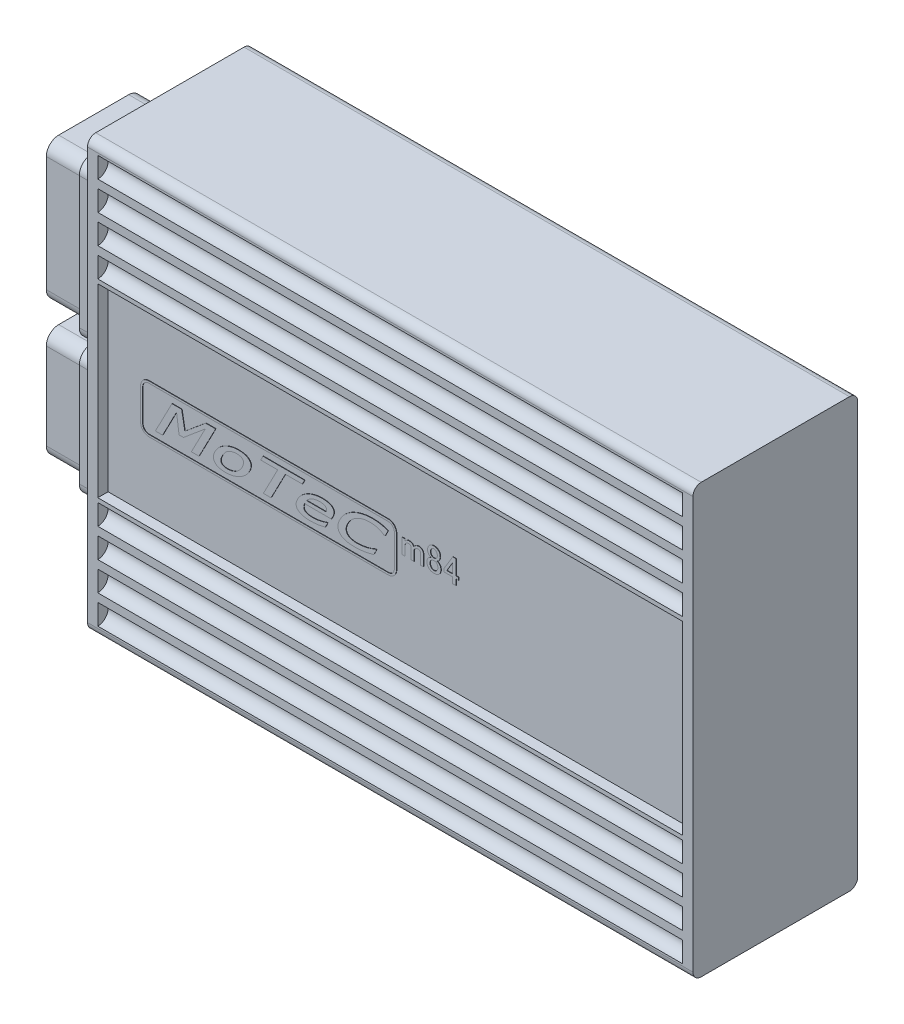
SolidWorks part; units mm, degrees
material "ｽﾁﾚﾝ ﾌﾞﾀｼﾞｴﾝｺﾞﾑ(SBR)"
ref_plane "正面" through (0, 0, 0) normal (0, 0, 1) x (1, 0, 0)
ref_plane "平面" through (0, 0, 0) normal (0, 1, 0) x (1, 0, 0)
ref_plane "右側面" through (0, 0, 0) normal (1, 0, 0) x (0, 0, -1)
sketch "ｽｹｯﾁ1" plane through (0, 0, 0) normal (0, 0, 1) x (1, 0, 0)
  line L1 (-73.5, -52) -> (73.5, -52)
  line L2 (-73.5, -52) -> (-73.5, 52)
  line L3 (-73.5, 52) -> (73.5, 52)
  line L4 (73.5, -52) -> (73.5, 52)
  line L5 (-73.5, -52) -> (73.5, 52) construction
  line L6 (-73.5, 52) -> (73.5, -52) construction
  point P0 (0, 0)
extrude "ﾎﾞｽ - 押し出し1" add sketch "ｽｹｯﾁ1" along normal blind 40
fillet "ﾌｨﾚｯﾄ1" radius 2 4 edges at (0, -52, 0) (0, -52, 40) (0, 52, 0) (0, 52, 40)
sketch "ｽｹｯﾁ5" plane through (0, 0, 0) normal (0, 0, -1) x (-1, 0, 0)
  line L0 (73.5, 50) -> (73.5, -50) construction
  line L1 (-73.5, 22.5) -> (73.5, 22.5)
  line L2 (-73.5, 22.5) -> (-73.5, -22.5)
  line L3 (-73.5, -22.5) -> (73.5, -22.5)
  line L4 (73.5, 22.5) -> (73.5, -22.5)
  line L5 (-73.5, 22.5) -> (73.5, -22.5) construction
  line L6 (-73.5, -22.5) -> (73.5, 22.5) construction
  point P0 (0, 0)
extrude "ｶｯﾄ - 押し出し1" cut sketch "ｽｹｯﾁ5" against normal blind 2.5
sketch "ｽｹｯﾁ6" plane through (-73.5, 0, 0) normal (-1, 0, 0) x (0, 0, 1)
  line L0 (0, 49.5) -> (0, 44.5)
  line L1 (0, 42.5) -> (0, 37.5)
  line L2 (0, 35.5) -> (0, 30.5)
  line L3 (0, 50) -> (0, 22.5) construction
  line L4 (0, 28.5) -> (0, 23.5)
  line L7 (40, 28.5) -> (40, 23.5)
  line L8 (40, 35.5) -> (40, 30.5)
  line L9 (40, 42.5) -> (40, 37.5)
  line L10 (40, 49.5) -> (40, 44.5)
  arc A0 (0, 44.5) -> (0, 49.5) centre (0, 47) ccw
  arc A1 (0, 37.5) -> (0, 42.5) centre (0, 40) ccw
  arc A2 (0, 30.5) -> (0, 35.5) centre (0, 33) ccw
  arc A3 (0, 23.5) -> (0, 28.5) centre (0, 26) ccw
  arc A4 (40, 23.5) -> (40, 28.5) centre (40, 26) cw
  arc A5 (40, 30.5) -> (40, 35.5) centre (40, 33) cw
  arc A6 (40, 37.5) -> (40, 42.5) centre (40, 40) cw
  arc A7 (40, 44.5) -> (40, 49.5) centre (40, 47) cw
extrude "ｶｯﾄ - 押し出し2" cut sketch "ｽｹｯﾁ6" against normal through all
mirror "ﾐﾗｰ1" about plane through (0, 0, 0) normal (0, 1, 0) of "ｶｯﾄ - 押し出し2"
sketch "ｽｹｯﾁ7" plane through (0, 0, 40) normal (0, 0, 1) x (1, 0, 0)
  line L0 (73.5, -23.5) -> (73.5, 23.5) construction
  line L1 (-73.5, -22.5) -> (73.5, -22.5)
  line L2 (-73.5, -22.5) -> (-73.5, 22.5)
  line L3 (-73.5, 22.5) -> (73.5, 22.5)
  line L4 (73.5, -22.5) -> (73.5, 22.5)
  line L5 (-73.5, -22.5) -> (73.5, 22.5) construction
  line L6 (-73.5, 22.5) -> (73.5, -22.5) construction
  point P0 (0, 0)
extrude "ｶｯﾄ - 押し出し3" cut sketch "ｽｹｯﾁ7" against normal blind 2.5
sketch "ｽｹｯﾁ8" plane through (-73.5, 0, 0) normal (-1, 0, 0) x (0, 0, 1)
  line L0 (2, -52) -> (38, -52)
  line L2 (40, -50) -> (40, 50)
  line L3 (38, 52) -> (2, 52)
  line L4 (0, 50) -> (0, -50)
  arc A0 (38, -52) -> (40, -50) centre (38, -50) ccw
  arc A1 (0, -50) -> (2, -52) centre (2, -50) ccw
  arc A2 (2, 52) -> (0, 50) centre (2, 50) ccw
  arc A3 (40, 50) -> (38, 52) centre (38, 50) ccw
  dimension "D1" = 2
extrude "ﾎﾞｽ - 押し出し4" add sketch "ｽｹｯﾁ8" against normal blind 2.5
sketch "ｽｹｯﾁ9" plane through (73.5, 0, 0) normal (1, 0, 0) x (0, 0, -1)
  line L0 (-38, -52) -> (-2, -52)
  line L2 (0, -50) -> (0, 50)
  line L3 (-2, 52) -> (-38, 52)
  line L4 (-40, 50) -> (-40, -50)
  arc A1 (-38, 52) -> (-40, 50) centre (-38, 50) ccw
  arc A2 (0, 50) -> (-2, 52) centre (-2, 50) ccw
  arc A3 (-2, -52) -> (0, -50) centre (-2, -50) ccw
  arc A4 (-40, -50) -> (-38, -52) centre (-38, -50) ccw
  dimension "D1" = 2
extrude "ﾎﾞｽ - 押し出し5" add sketch "ｽｹｯﾁ9" against normal blind 2.5
sketch "ｽｹｯﾁ10" plane through (0, 0, 37.5) normal (0, 0, 1) x (1, 0, 0)
  line L0 (-61, 5.38) -> (-2.9, 5.38)
  line L1 (-61, 5.88) -> (-2.9, 5.88)
  line L2 (-48.818, -3.88) -> (-50.6846, -3.88)
  line L3 (-61, -5.38) -> (-2.9, -5.38)
  line L4 (-50.6846, -3.88) -> (-47.2953, 2.6347)
  line L5 (-62.5, -3.88) -> (-62.5, 3.88)
  line L6 (-63, -3.88) -> (-63, 3.88)
  line L7 (-1.4, 3.88) -> (-1.4, -3.88)
  line L8 (-2.9, -5.88) -> (-61, -5.88)
  line L9 (-0.9, 3.88) -> (-0.9, -3.88)
  line L10 (-47.2953, 2.6347) -> (-52.5742, -1.8169)
  line L11 (-52.5742, -1.8169) -> (-53.6672, -1.8169)
  line L12 (-53.6672, -1.8169) -> (-54.2704, 2.6347)
  line L13 (-54.2704, 2.6347) -> (-57.6598, -3.88)
  line L14 (-57.6598, -3.88) -> (-59.4281, -3.88)
  line L15 (-59.4281, -3.88) -> (-55.3895, 3.8811)
  line L16 (-55.3895, 3.8811) -> (-53.0363, 3.8811)
  line L17 (-53.0363, 3.8811) -> (-52.2641, -0.3464)
  line L18 (-52.2641, -0.3464) -> (-47.1924, 3.8811)
  line L19 (-47.1924, 3.8811) -> (-44.7793, 3.8811)
  line L20 (-44.7793, 3.8811) -> (-48.818, -3.88)
  line L21 (-23.7279, 2.8005) -> (-27.8541, 2.8005)
  line L22 (-27.8541, 2.8005) -> (-31.3309, -3.88)
  line L23 (-31.3309, -3.88) -> (-33.1975, -3.88)
  line L24 (-33.1975, -3.88) -> (-29.7207, 2.8005)
  line L25 (-29.7207, 2.8005) -> (-33.8469, 2.8005)
  line L26 (-33.8469, 2.8005) -> (-33.285, 3.8811)
  line L27 (-33.285, 3.8811) -> (-23.1661, 3.8811)
  line L28 (-23.1661, 3.8811) -> (-23.7279, 2.8005)
  line L29 (-16.6837, -1.031) -> (-23.1677, -1.031)
  line L30 (-17.8457, -2.3081) -> (-17.5448, -2.3081)
  line L31 (-17.5448, -2.3081) -> (-18.1512, -3.4717)
  line L32 (-16.3675, -0.4231) -> (-16.6837, -1.031)
  line L33 (-22.7071, -0.1468) -> (-17.9915, -0.1468)
  line L34 (-2.9053, 3.3592) -> (-3.6052, 2.0145)
  line L35 (-3.6052, 2.0145) -> (-3.9475, 2.0145)
  line L36 (-6.0306, -2.0134) -> (-5.7005, -2.0134)
  line L37 (-5.7005, -2.0134) -> (-6.3944, -3.3458)
  arc A0 (-62.5, -3.88) -> (-61, -5.38) centre (-61, -3.88) ccw
  arc A1 (-63, -3.88) -> (-61, -5.88) centre (-61, -3.88) ccw
  arc A2 (-2.9, -5.38) -> (-1.4, -3.88) centre (-2.9, -3.88) ccw
  arc A3 (-2.9, -5.88) -> (-0.9, -3.88) centre (-2.9, -3.88) ccw
  arc A4 (-0.9, 3.88) -> (-2.9, 5.88) centre (-2.9, 3.88) ccw
  arc A5 (-1.4, 3.88) -> (-2.9, 5.38) centre (-2.9, 3.88) ccw
  arc A6 (-61, 5.38) -> (-62.5, 3.88) centre (-61, 3.88) ccw
  arc A7 (-61, 5.88) -> (-63, 3.88) centre (-61, 3.88) ccw
  spline S0 degree 3 poles (-36.5777, -0.9358) (-36.7009, -1.173) (-36.9152, -1.5135) (-37.2513, -1.9317) (-37.5302, -2.2278) (-37.8372, -2.5041) (-38.1693, -2.764) (-38.5283, -3.0057) (-38.9122, -3.2263) (-39.3132, -3.4265) (-39.7277, -3.6013) (-40.1536, -3.7457) (-40.5887, -3.8684) (-41.0349, -3.9619) (-41.649, -4.05) (-42.1174, -4.0762) (-42.4323, -4.0765) knots 0 0 0 0 0.11486 0.17245 0.230506 0.289545 0.349887 0.411704 0.475483 0.540129 0.604325 0.668756 0.733403 0.798605 0.864633 1 1 1 1
  spline S1 degree 3 poles (-42.4323, -4.0765) (-42.5834, -4.0783) (-42.8056, -4.0683) (-43.0953, -4.0494) (-43.2985, -4.0256) (-43.4923, -3.9973) (-43.6765, -3.96) (-43.8518, -3.9174) (-44.0177, -3.8681) (-44.1746, -3.8138) (-44.3211, -3.7497) (-44.4591, -3.6817) (-44.587, -3.6058) (-44.7062, -3.5246) (-44.8151, -3.4352) (-44.9152, -3.3398) (-45.0063, -3.2387) (-45.0858, -3.1309) (-45.1562, -3.0187) (-45.2118, -2.9001) (-45.2596, -2.778) (-45.2917, -2.6499) (-45.3182, -2.5179) (-45.3269, -2.3804) (-45.3297, -2.2389) (-45.3179, -2.0927) (-45.2961, -1.9415) (-45.2643, -1.7849) (-45.2188, -1.6238) (-45.1639, -1.4575) (-45.0707, -1.2253) (-44.9886, -1.0518) (-44.9282, -0.9358) knots 0 0 0 0 0.08649 0.127322 0.166248 0.203584 0.23944 0.273835 0.30684 0.338533 0.36885 0.398333 0.426574 0.453963 0.480825 0.507145 0.533083 0.558634 0.58376 0.608791 0.633551 0.65871 0.684341 0.710499 0.737457 0.765367 0.794373 0.824886 0.856804 0.89016 0.925145 1 1 1 1
  spline S2 degree 3 poles (-44.9282, -0.9358) (-44.8022, -0.6955) (-44.5877, -0.3482) (-44.2489, 0.0764) (-43.9702, 0.375) (-43.6668, 0.6536) (-43.3382, 0.9124) (-42.9843, 1.1516) (-42.6081, 1.372) (-42.2138, 1.5683) (-41.8079, 1.7417) (-41.3903, 1.8851) (-40.9637, 2.0059) (-40.5266, 2.0973) (-39.9262, 2.1872) (-39.4676, 2.2089) (-39.1596, 2.211) knots 0 0 0 0 0.117897 0.176741 0.23572 0.295189 0.355492 0.41727 0.480633 0.544754 0.608501 0.672263 0.736447 0.800971 0.86614 1 1 1 1
  spline S3 degree 3 poles (-39.1596, 2.211) (-39.0055, 2.212) (-38.7785, 2.2044) (-38.4828, 2.1817) (-38.2753, 2.1594) (-38.0778, 2.128) (-37.8898, 2.0917) (-37.7107, 2.0491) (-37.5419, 1.998) (-37.3816, 1.9418) (-37.2315, 1.8774) (-37.0912, 1.8064) (-36.9598, 1.7299) (-36.8387, 1.645) (-36.7263, 1.5549) (-36.624, 1.4574) (-36.5325, 1.3533) (-36.4501, 1.2439) (-36.3803, 1.1288) (-36.3192, 1.0103) (-36.2719, 0.8865) (-36.2349, 0.7587) (-36.2085, 0.6268) (-36.1952, 0.49) (-36.1917, 0.3489) (-36.2017, 0.2032) (-36.2217, 0.0534) (-36.2531, -0.1007) (-36.2938, -0.26) (-36.3488, -0.4229) (-36.4364, -0.6522) (-36.5191, -0.8216) (-36.5777, -0.9358) knots 0 0 0 0 0.087469 0.128832 0.16828 0.205905 0.2423 0.276956 0.310309 0.342367 0.373332 0.402945 0.431585 0.459541 0.4868 0.513298 0.539635 0.565367 0.590919 0.615986 0.640903 0.665995 0.691455 0.717145 0.74387 0.771515 0.799937 0.829554 0.860759 0.893179 0.927103 1 1 1 1
  spline S4 degree 3 poles (-38.346, -0.9358) (-38.2574, -0.7704) (-38.1489, -0.5248) (-38.0457, -0.2002) (-38.0049, 0.0143) (-37.9926, 0.211) (-38.0094, 0.3913) (-38.0597, 0.5536) (-38.1369, 0.6994) (-38.2448, 0.8249) (-38.3747, 0.9354) (-38.5316, 1.0255) (-38.7113, 1.1012) (-38.9167, 1.1584) (-39.2379, 1.2147) (-39.4932, 1.2305) (-39.6708, 1.2286) knots 0 0 0 0 0.165351 0.236136 0.299935 0.35732 0.409486 0.458578 0.506215 0.55393 0.603552 0.655936 0.712748 0.775154 0.843472 1 1 1 1
  spline S5 degree 3 poles (-39.6708, 1.2286) (-39.8529, 1.2297) (-40.1234, 1.2126) (-40.4773, 1.1597) (-40.7328, 1.103) (-40.9807, 1.0286) (-41.2218, 0.9397) (-41.4561, 0.8354) (-41.6821, 0.7134) (-41.9013, 0.5755) (-42.11, 0.417) (-42.309, 0.2388) (-42.4999, 0.0427) (-42.6788, -0.1755) (-42.9131, -0.4938) (-43.0653, -0.7549) (-43.1599, -0.9358) knots 0 0 0 0 0.125748 0.186879 0.246987 0.306363 0.365517 0.424368 0.483349 0.542766 0.603061 0.664139 0.727124 0.791879 0.858893 1 1 1 1
  spline S6 degree 3 poles (-43.1599, -0.9358) (-43.2444, -1.1024) (-43.3583, -1.3453) (-43.4595, -1.6697) (-43.5022, -1.8833) (-43.5179, -2.0794) (-43.5036, -2.2592) (-43.4591, -2.4214) (-43.3855, -2.5663) (-43.2836, -2.6915) (-43.1582, -2.8004) (-43.0096, -2.8929) (-42.8366, -2.9656) (-42.6417, -3.0243) (-42.335, -3.08) (-42.0911, -3.096) (-41.9211, -3.0941) knots 0 0 0 0 0.168476 0.240795 0.305611 0.364297 0.417506 0.467272 0.514892 0.562763 0.611762 0.663944 0.719687 0.780349 0.846975 1 1 1 1
  spline S7 degree 3 poles (-41.9211, -3.0941) (-41.7331, -3.0918) (-41.4531, -3.0796) (-41.0877, -3.0195) (-40.8225, -2.963) (-40.5649, -2.885) (-40.3148, -2.7913) (-40.0706, -2.6823) (-39.8349, -2.5547) (-39.6073, -2.4111) (-39.3924, -2.2487) (-39.1871, -2.0723) (-38.995, -1.8776) (-38.8135, -1.6672) (-38.5852, -1.3596) (-38.4377, -1.1088) (-38.346, -0.9358) knots 0 0 0 0 0.128096 0.190164 0.251852 0.312564 0.373178 0.433506 0.494435 0.555497 0.616445 0.67768 0.739494 0.802466 0.866689 1 1 1 1
  spline S8 degree 3 poles (-23.1677, -1.031) (-23.239, -1.1708) (-23.3273, -1.3838) (-23.38, -1.6756) (-23.3836, -1.8779) (-23.3558, -2.064) (-23.2898, -2.2835) (-23.1916, -2.4213) (-23.1124, -2.4939) knots 0 0 0 0 0.300432 0.436419 0.564515 0.685087 0.794857 1 1 1 1
  spline S9 degree 3 poles (-23.1124, -2.4939) (-23.0171, -2.5853) (-22.8472, -2.6978) (-22.5932, -2.8134) (-22.3737, -2.881) (-22.1311, -2.9328) (-21.7617, -2.9823) (-21.4713, -2.9964) (-21.2704, -2.9958) knots 0 0 0 0 0.202 0.310705 0.427794 0.554064 0.691352 1 1 1 1
  spline S10 degree 3 poles (-21.2704, -2.9958) (-20.9645, -2.9964) (-20.4966, -2.9651) (-19.8657, -2.8697) (-19.4578, -2.787) (-19.1335, -2.7124) (-18.904, -2.6537) (-18.6896, -2.5968) (-18.4904, -2.5414) (-18.3075, -2.4814) (-18.0917, -2.4113) (-17.9411, -2.3484) (-17.8457, -2.3081) knots 0 0 0 0 0.261145 0.399928 0.544803 0.616587 0.684226 0.7471 0.806182 0.860786 0.911516 1 1 1 1
  spline S11 degree 3 poles (-18.1512, -3.4717) (-18.475, -3.5472) (-18.9516, -3.6513) (-19.5758, -3.7713) (-20.0167, -3.8464) (-20.4491, -3.9062) (-21.0272, -3.9606) (-21.4634, -3.9803) (-21.7554, -3.9782) knots 0 0 0 0 0.273424 0.401082 0.522686 0.641161 0.759937 1 1 1 1
  spline S12 degree 3 poles (-21.7554, -3.9782) (-21.9325, -3.9782) (-22.1927, -3.9728) (-22.5319, -3.952) (-22.7704, -3.9305) (-22.9983, -3.9034) (-23.2158, -3.8692) (-23.4231, -3.8303) (-23.6188, -3.7821) (-23.8044, -3.7301) (-23.9792, -3.6721) (-24.1438, -3.6078) (-24.2976, -3.5371) (-24.4413, -3.4607) (-24.5728, -3.3758) (-24.6951, -3.287) (-24.8059, -3.1914) (-24.9057, -3.0909) (-24.9926, -2.984) (-25.0668, -2.8714) (-25.1282, -2.7529) (-25.1775, -2.6295) (-25.2152, -2.5012) (-25.2374, -2.3672) (-25.2483, -2.228) (-25.2465, -2.0837) (-25.2323, -1.9339) (-25.2059, -1.779) (-25.1677, -1.6188) (-25.1143, -1.4541) (-25.0259, -1.2206) (-24.9444, -1.0463) (-24.8838, -0.9297) knots 0 0 0 0 0.093747 0.137709 0.179862 0.220513 0.259166 0.296403 0.332074 0.365856 0.398404 0.429538 0.459352 0.487951 0.5156 0.542146 0.567881 0.592971 0.617041 0.640704 0.664206 0.687544 0.710946 0.734858 0.759308 0.78477 0.811155 0.838897 0.867868 0.898277 0.930422 1 1 1 1
  spline S13 degree 3 poles (-24.8838, -0.9297) (-24.7596, -0.6889) (-24.54, -0.3451) (-24.1967, 0.0779) (-23.9084, 0.374) (-23.5931, 0.6518) (-23.2507, 0.9114) (-22.879, 1.1507) (-22.4832, 1.3708) (-22.0683, 1.5667) (-21.6416, 1.7397) (-21.2059, 1.8857) (-20.7601, 2.0035) (-20.3058, 2.0979) (-19.6825, 2.1863) (-19.2078, 2.2093) (-18.8895, 2.211) knots 0 0 0 0 0.114335 0.17179 0.229874 0.288677 0.349154 0.411205 0.475256 0.540323 0.604903 0.66963 0.734274 0.799596 0.865529 1 1 1 1
  spline S14 degree 3 poles (-18.8895, 2.211) (-18.6048, 2.2099) (-18.1943, 2.1957) (-17.6759, 2.1191) (-17.3417, 2.0438) (-17.0445, 1.9461) (-16.7843, 1.8273) (-16.5608, 1.6854) (-16.3763, 1.5207) (-16.2307, 1.3359) (-16.1253, 1.1324) (-16.062, 0.9113) (-16.0409, 0.6734) (-16.0638, 0.4205) (-16.1471, 0.0427) (-16.2705, -0.2361) (-16.3675, -0.4231) knots 0 0 0 0 0.180062 0.258847 0.330846 0.396281 0.456168 0.511145 0.562887 0.611718 0.659004 0.706791 0.756144 0.809012 0.866596 1 1 1 1
  spline S15 degree 3 poles (-17.9915, -0.1468) (-17.9461, -0.0555) (-17.8865, 0.0815) (-17.8527, 0.2692) (-17.8447, 0.3975) (-17.8607, 0.5196) (-17.8964, 0.6349) (-17.9525, 0.7434) (-18.0288, 0.8451) (-18.1292, 0.9365) (-18.2534, 1.0168) (-18.4034, 1.0814) (-18.5763, 1.1374) (-18.7753, 1.1766) (-19.0885, 1.2199) (-19.3376, 1.2281) (-19.5112, 1.2286) knots 0 0 0 0 0.116957 0.168662 0.217232 0.263196 0.308491 0.3545 0.402079 0.452957 0.508728 0.570212 0.638975 0.71601 0.801566 1 1 1 1
  spline S16 degree 3 poles (-19.5112, 1.2286) (-19.6901, 1.2296) (-19.9551, 1.2158) (-20.3024, 1.173) (-20.5519, 1.1269) (-20.7942, 1.0681) (-21.0289, 0.9984) (-21.2559, 0.9133) (-21.473, 0.8155) (-21.6796, 0.7097) (-21.8724, 0.5999) (-22.0503, 0.4864) (-22.2113, 0.3673) (-22.3597, 0.2473) (-22.5306, 0.0813) (-22.6436, -0.052) (-22.7071, -0.1468) knots 0 0 0 0 0.148913 0.22062 0.291229 0.360047 0.428112 0.494978 0.561724 0.626315 0.68814 0.746401 0.801873 0.85484 0.905156 1 1 1 1
  spline S17 degree 3 poles (-6.3944, -3.3458) (-6.5902, -3.3974) (-6.8702, -3.4618) (-7.2185, -3.5552) (-7.4427, -3.6129) (-7.6661, -3.6705) (-8.0166, -3.7476) (-8.2963, -3.8041) (-8.4943, -3.8416) knots 0 0 0 0 0.281526 0.399182 0.501308 0.603258 0.719903 1 1 1 1
  spline S18 degree 3 poles (-8.4943, -3.8416) (-8.8676, -3.9077) (-9.3444, -3.9804) (-9.9296, -4.0402) (-10.362, -4.069) (-10.6924, -4.0756) (-10.9166, -4.0765) knots 0 0 0 0 0.466732 0.593333 0.724013 1 1 1 1
  spline S19 degree 3 poles (-10.9166, -4.0765) (-11.1224, -4.0785) (-11.4255, -4.0686) (-11.8221, -4.0444) (-12.1026, -4.0187) (-12.3717, -3.9842) (-12.6302, -3.9457) (-12.8771, -3.8954) (-13.1137, -3.8416) (-13.3375, -3.777) (-13.5489, -3.7043) (-13.7484, -3.6255) (-13.9349, -3.5367) (-14.1073, -3.4372) (-14.3203, -3.2993) (-14.4632, -3.1767) (-14.5515, -3.091) knots 0 0 0 0 0.160141 0.235948 0.30913 0.379362 0.447054 0.512417 0.575391 0.635885 0.693558 0.74931 0.80274 0.854105 0.904135 1 1 1 1
  spline S20 degree 3 poles (-14.5515, -3.091) (-14.6332, -3.0081) (-14.7451, -2.8747) (-14.8665, -2.6775) (-14.9392, -2.5203) (-14.9998, -2.3557) (-15.0445, -2.1824) (-15.0729, -2.0004) (-15.0888, -1.8101) (-15.0872, -1.6112) (-15.0661, -1.4045) (-15.0293, -1.1901) (-14.9748, -0.9675) (-14.9028, -0.7377) (-14.7767, -0.413) (-14.6637, -0.1699) (-14.5792, -0.0071) knots 0 0 0 0 0.105347 0.15689 0.209093 0.261831 0.315407 0.370754 0.428362 0.488101 0.550445 0.616222 0.684847 0.757639 0.834008 1 1 1 1
  spline S21 degree 3 poles (-14.5792, -0.0071) (-14.4951, 0.1549) (-14.3581, 0.3917) (-14.1569, 0.6954) (-13.9973, 0.9172) (-13.8265, 1.1317) (-13.6473, 1.3406) (-13.4578, 1.5424) (-13.1913, 1.8022) (-12.8362, 2.1099) (-12.2254, 2.5699) (-11.7239, 2.8586) (-11.3786, 3.0338) knots 0 0 0 0 0.121978 0.18268 0.243425 0.304524 0.365875 0.427326 0.489476 0.614555 0.741086 1 1 1 1
  spline S22 degree 3 poles (-11.3786, 3.0338) (-11.0336, 3.2049) (-10.496, 3.4343) (-9.7453, 3.668) (-9.1567, 3.8174) (-8.5507, 3.9325) (-7.7204, 4.0477) (-7.0883, 4.0758) (-6.6645, 4.0776) knots 0 0 0 0 0.237239 0.359144 0.483968 0.611049 0.738924 1 1 1 1
  spline S23 degree 3 poles (-6.6645, 4.0776) (-6.3521, 4.0784) (-5.8883, 4.0593) (-5.2793, 3.995) (-4.8316, 3.9292) (-4.3774, 3.8355) (-3.7276, 3.6632) (-3.2372, 3.49) (-2.9053, 3.3592) knots 0 0 0 0 0.243327 0.361127 0.476764 0.595548 0.722064 1 1 1 1
  spline S24 degree 3 poles (-3.9475, 2.0145) (-4.1771, 2.184) (-4.5416, 2.4084) (-5.0614, 2.6382) (-5.4679, 2.7721) (-5.8967, 2.874) (-6.5232, 2.9708) (-7.0117, 2.9991) (-7.3461, 2.9969) knots 0 0 0 0 0.237578 0.354907 0.472536 0.593451 0.721574 1 1 1 1
  spline S25 degree 3 poles (-7.3461, 2.9969) (-7.6219, 2.9979) (-8.0311, 2.9755) (-8.5665, 2.9016) (-8.9542, 2.8232) (-9.3368, 2.7185) (-9.8553, 2.5457) (-10.2318, 2.368) (-10.4822, 2.2417) knots 0 0 0 0 0.253906 0.376619 0.497274 0.617832 0.741623 1 1 1 1
  spline S26 degree 3 poles (-10.4822, 2.2417) (-10.7045, 2.1261) (-11.028, 1.9227) (-11.4317, 1.6025) (-11.7296, 1.3332) (-12.0114, 1.0365) (-12.3621, 0.6006) (-12.5845, 0.2402) (-12.7156, -0.0117) knots 0 0 0 0 0.233293 0.354756 0.479582 0.607001 0.735458 1 1 1 1
  spline S27 degree 3 poles (-12.7156, -0.0117) (-12.7817, -0.1391) (-12.8725, -0.3274) (-12.9672, -0.5803) (-13.0257, -0.7553) (-13.0665, -0.9239) (-13.0951, -1.0849) (-13.1092, -1.2379) (-13.1092, -1.4273) (-13.0816, -1.6452) (-13.0027, -1.9554) (-12.8863, -2.1582) (-12.7862, -2.2682) knots 0 0 0 0 0.179369 0.260704 0.337327 0.409738 0.477214 0.541403 0.601498 0.713544 0.814809 1 1 1 1
  spline S28 degree 3 poles (-12.7862, -2.2682) (-12.6661, -2.3989) (-12.4496, -2.5673) (-12.1148, -2.7325) (-11.8285, -2.8305) (-11.5157, -2.9045) (-11.0545, -2.9772) (-10.6945, -2.996) (-10.4484, -2.9958) knots 0 0 0 0 0.211163 0.323577 0.443788 0.571197 0.706507 1 1 1 1
  spline S29 degree 3 poles (-10.4484, -2.9958) (-10.0792, -2.9962) (-9.5258, -2.9642) (-8.7927, -2.864) (-8.244, -2.7575) (-7.6933, -2.6209) (-6.9482, -2.3886) (-6.3948, -2.1771) (-6.0306, -2.0134) knots 0 0 0 0 0.24289 0.364219 0.486645 0.610525 0.737368 1 1 1 1
sketch "ｽｹｯﾁ11" plane through (0, 0, 37.5) normal (0, 0, 1) x (1, 0, 0)
  line L0 (1.1441, 0.0981) -> (0.448, 0.0981)
  line L1 (0.448, 0.0981) -> (0.448, 3.7593)
  line L2 (0.448, 3.7593) -> (1.1441, 3.7593)
  line L3 (1.1441, 3.7593) -> (1.1441, 3.2036)
  line L4 (5.6553, 2.8113) -> (5.6553, 0.0981)
  line L5 (5.6553, 0.0981) -> (4.9592, 0.0981)
  line L6 (4.9592, 0.0981) -> (4.9592, 2.6806)
  line L7 (3.3997, 2.419) -> (3.3997, 0.0981)
  line L8 (3.3997, 0.0981) -> (2.7036, 0.0981)
  line L9 (2.7036, 0.0981) -> (2.7036, 2.6479)
  line L10 (1.1441, 2.3864) -> (1.1441, 0.0981)
  line L11 (8.9655, 3.0075) -> (8.9655, 2.9421)
  line L12 (7.4618, 2.9421) -> (7.4618, 3.0075)
  line L13 (12.7902, 5.7534) -> (13.5421, 5.7534)
  line L14 (13.5421, 5.7534) -> (13.5421, 2.1575)
  line L15 (13.5421, 2.1575) -> (14.2286, 2.1575)
  line L16 (14.2286, 2.1575) -> (14.2286, 1.5388)
  line L17 (14.2286, 1.5388) -> (13.5421, 1.5388)
  line L18 (13.5421, 1.5388) -> (13.5421, 0.0981)
  line L19 (13.5421, 0.0981) -> (12.7684, 0.0981)
  line L20 (12.7684, 0.0981) -> (12.7684, 1.5388)
  line L21 (12.7684, 1.5388) -> (10.6, 1.5388)
  line L22 (10.6, 1.5388) -> (10.6, 2.1902)
  line L23 (10.6, 2.1902) -> (12.7902, 5.7534)
  line L24 (12.7684, 4.5439) -> (11.3192, 2.1575)
  line L25 (11.3192, 2.1575) -> (12.7684, 2.1575)
  line L26 (12.7684, 2.1575) -> (12.7684, 4.5439)
  spline S0 degree 3 poles (1.1441, 3.2036) (1.2091, 3.3006) (1.3165, 3.4324) (1.4761, 3.5832) (1.5982, 3.6709) (1.7237, 3.7398) (1.8965, 3.8054) (2.0336, 3.8248) (2.1248, 3.8247) knots 0 0 0 0 0.289076 0.420056 0.543346 0.660649 0.774007 1 1 1 1
  spline S1 degree 3 poles (2.1248, 3.8247) (2.2225, 3.8255) (2.3653, 3.8154) (2.5475, 3.7813) (2.6714, 3.7462) (2.7859, 3.7001) (2.9253, 3.6249) (3.0183, 3.5525) (3.0728, 3.4978) knots 0 0 0 0 0.28435 0.416051 0.539631 0.658871 0.775162 1 1 1 1
  spline S2 degree 3 poles (3.0728, 3.4978) (3.1259, 3.4441) (3.225, 3.3321) (3.3007, 3.2031) (3.3344, 3.1382) knots 0 0 0 0 0.508066 1 1 1 1
  spline S3 degree 3 poles (3.3344, 3.1382) (3.4009, 3.2461) (3.5142, 3.3952) (3.6946, 3.5595) (3.8391, 3.6553) (3.9921, 3.7317) (4.2138, 3.8066) (4.3918, 3.8235) (4.5112, 3.8247) knots 0 0 0 0 0.266156 0.390354 0.510676 0.628903 0.748675 1 1 1 1
  spline S4 degree 3 poles (4.5112, 3.8247) (4.5937, 3.8239) (4.715, 3.8171) (4.8701, 3.7856) (4.9763, 3.7531) (5.0759, 3.7116) (5.1981, 3.6443) (5.2797, 3.579) (5.3284, 3.5305) knots 0 0 0 0 0.277854 0.406706 0.531659 0.650908 0.768781 1 1 1 1
  spline S5 degree 3 poles (5.3284, 3.5305) (5.3803, 3.4787) (5.4513, 3.3967) (5.5288, 3.2784) (5.576, 3.1891) (5.6103, 3.0972) (5.6454, 2.9726) (5.6558, 2.876) (5.6553, 2.8113) knots 0 0 0 0 0.271081 0.399345 0.522112 0.643458 0.761079 1 1 1 1
  spline S6 degree 3 poles (4.9592, 2.6806) (4.9575, 2.7409) (4.949, 2.8568) (4.9009, 2.9629) (4.8708, 3.0075) knots 0 0 0 0 0.529898 1 1 1 1
  spline S7 degree 3 poles (4.8708, 3.0075) (4.81, 3.0685) (4.6691, 3.1722) (4.4969, 3.2038) (4.4131, 3.2036) knots 0 0 0 0 0.507506 1 1 1 1
  spline S8 degree 3 poles (4.4131, 3.2036) (4.3398, 3.2028) (4.2315, 3.1955) (4.0927, 3.1647) (3.9963, 3.131) (3.9039, 3.0907) (3.7882, 3.0211) (3.7089, 2.9578) (3.6613, 2.9094) knots 0 0 0 0 0.265315 0.391024 0.512886 0.634416 0.754828 1 1 1 1
  spline S9 degree 3 poles (3.6613, 2.9094) (3.5876, 2.833) (3.4593, 2.6878) (3.4011, 2.5024) (3.3997, 2.419) knots 0 0 0 0 0.564258 1 1 1 1
  spline S10 degree 3 poles (2.7036, 2.6479) (2.7041, 2.7153) (2.672, 2.8568) (2.5978, 2.9811) (2.5498, 3.0402) knots 0 0 0 0 0.468245 1 1 1 1
  spline S11 degree 3 poles (2.5498, 3.0402) (2.4931, 3.098) (2.3343, 3.1836) (2.1559, 3.2052) (2.0595, 3.2036) knots 0 0 0 0 0.45309 1 1 1 1
  spline S12 degree 3 poles (2.0595, 3.2036) (1.9447, 3.2054) (1.7132, 3.1598) (1.5193, 3.0255) (1.4384, 2.9421) knots 0 0 0 0 0.496526 1 1 1 1
  spline S13 degree 3 poles (1.4384, 2.9421) (1.3545, 2.8562) (1.2127, 2.6903) (1.1432, 2.4818) (1.1441, 2.3864) knots 0 0 0 0 0.561835 1 1 1 1
  spline S14 degree 3 poles (6.6772, 4.1843) (6.6768, 4.2995) (6.6912, 4.4688) (6.7381, 4.6867) (6.7896, 4.838) (6.8539, 4.9823) (6.9595, 5.1641) (7.0598, 5.287) (7.1349, 5.3611) knots 0 0 0 0 0.266281 0.391515 0.514598 0.635338 0.756207 1 1 1 1
  spline S15 degree 3 poles (7.1349, 5.3611) (7.2002, 5.4253) (7.3073, 5.5139) (7.4705, 5.6021) (7.6011, 5.6584) (7.7419, 5.7001) (7.9453, 5.7439) (8.1052, 5.7528) (8.2136, 5.7534) knots 0 0 0 0 0.233399 0.350616 0.471182 0.594645 0.723766 1 1 1 1
  spline S16 degree 3 poles (8.2136, 5.7534) (8.3232, 5.7551) (8.4841, 5.7404) (8.6912, 5.6974) (8.8344, 5.6494) (8.9701, 5.5899) (9.1412, 5.4928) (9.2549, 5.3974) (9.3251, 5.3284) knots 0 0 0 0 0.268573 0.395226 0.518308 0.638476 0.758247 1 1 1 1
  spline S17 degree 3 poles (9.3251, 5.3284) (9.3942, 5.2575) (9.4892, 5.1424) (9.5874, 4.969) (9.6459, 4.8292) (9.694, 4.6812) (9.7374, 4.466) (9.7518, 4.2987) (9.75, 4.1843) knots 0 0 0 0 0.237237 0.354867 0.475589 0.599283 0.726563 1 1 1 1
  spline S18 degree 3 poles (9.75, 4.1843) (9.7496, 4.0948) (9.7399, 3.9612) (9.6961, 3.7908) (9.6544, 3.6685) (9.5976, 3.5525) (9.5084, 3.4007) (9.4204, 3.3) (9.3578, 3.2363) knots 0 0 0 0 0.255144 0.378267 0.499952 0.622216 0.745323 1 1 1 1
  spline S19 degree 3 poles (9.3578, 3.2363) (9.3031, 3.1841) (9.1835, 3.0859) (9.0392, 3.0294) (8.9655, 3.0075) knots 0 0 0 0 0.495336 1 1 1 1
  spline S20 degree 3 poles (8.9655, 2.9421) (9.0661, 2.92) (9.2702, 2.8364) (9.4397, 2.6957) (9.5212, 2.6152) knots 0 0 0 0 0.472373 1 1 1 1
  spline S21 degree 3 poles (9.5212, 2.6152) (9.5855, 2.5508) (9.6734, 2.4449) (9.7619, 2.2847) (9.8183, 2.1578) (9.86, 2.0219) (9.904, 1.8266) (9.9129, 1.6731) (9.9135, 1.5691) knots 0 0 0 0 0.238094 0.356648 0.477581 0.600363 0.727833 1 1 1 1
  spline S22 degree 3 poles (9.9135, 1.5691) (9.9138, 1.4636) (9.8992, 1.3074) (9.852, 1.1064) (9.8021, 0.9634) (9.7365, 0.8269) (9.6294, 0.6512) (9.5306, 0.5307) (9.4558, 0.4577) knots 0 0 0 0 0.256258 0.379192 0.500731 0.623509 0.746244 1 1 1 1
  spline S23 degree 3 poles (9.4558, 0.4577) (9.3839, 0.3872) (9.2639, 0.2913) (9.0813, 0.1952) (8.9312, 0.1362) (8.7694, 0.0881) (8.5294, 0.0453) (8.3421, 0.0307) (8.2136, 0.0327) knots 0 0 0 0 0.224285 0.339224 0.458169 0.582683 0.714303 1 1 1 1
  spline S24 degree 3 poles (8.2136, 0.0327) (8.0851, 0.0307) (7.8978, 0.0453) (7.6578, 0.0881) (7.496, 0.1362) (7.346, 0.1952) (7.1634, 0.2913) (7.0434, 0.3872) (6.9714, 0.4577) knots 0 0 0 0 0.285697 0.417317 0.541831 0.660776 0.775715 1 1 1 1
  spline S25 degree 3 poles (6.9714, 0.4577) (6.8964, 0.5307) (6.7982, 0.6513) (6.6904, 0.8266) (6.627, 0.964) (6.5748, 1.1061) (6.5284, 1.3075) (6.5133, 1.4635) (6.5138, 1.5691) knots 0 0 0 0 0.253779 0.376526 0.498895 0.620773 0.743719 1 1 1 1
  spline S26 degree 3 poles (6.5138, 1.5691) (6.5144, 1.6731) (6.5233, 1.8266) (6.5672, 2.0219) (6.6089, 2.1578) (6.6653, 2.2847) (6.7538, 2.4449) (6.8418, 2.5508) (6.906, 2.6152) knots 0 0 0 0 0.272167 0.399637 0.522419 0.643352 0.761906 1 1 1 1
  spline S27 degree 3 poles (6.906, 2.6152) (6.9876, 2.6957) (7.157, 2.8364) (7.3611, 2.92) (7.4618, 2.9421) knots 0 0 0 0 0.527627 1 1 1 1
  spline S28 degree 3 poles (7.4618, 3.0075) (7.3877, 3.0309) (7.2361, 3.1183) (7.1052, 3.2335) (7.0368, 3.3017) knots 0 0 0 0 0.44402 1 1 1 1
  spline S29 degree 3 poles (7.0368, 3.3017) (6.9775, 3.359) (6.8997, 3.4543) (6.8161, 3.5935) (6.7647, 3.7015) (6.7261, 3.815) (6.6881, 3.9751) (6.6777, 4.1) (6.6772, 4.1843) knots 0 0 0 0 0.252388 0.374951 0.496631 0.618235 0.741494 1 1 1 1
  spline S30 degree 3 poles (8.2136, 5.165) (8.1109, 5.1645) (7.9026, 5.1302) (7.7302, 5.0084) (7.6579, 4.9362) knots 0 0 0 0 0.501621 1 1 1 1
  spline S31 degree 3 poles (7.6579, 4.9362) (7.6128, 4.8936) (7.5577, 4.8176) (7.4959, 4.7079) (7.4599, 4.6164) (7.4303, 4.519) (7.4054, 4.3741) (7.3943, 4.2619) (7.3964, 4.1843) knots 0 0 0 0 0.226302 0.342995 0.461285 0.586435 0.716023 1 1 1 1
  spline S32 degree 3 poles (7.3964, 4.1843) (7.394, 4.1115) (7.4059, 4.0058) (7.43, 3.8692) (7.4606, 3.7766) (7.4959, 3.6885) (7.558, 3.5813) (7.614, 3.5078) (7.6579, 3.4651) knots 0 0 0 0 0.276896 0.405601 0.528379 0.64854 0.7672 1 1 1 1
  spline S33 degree 3 poles (7.6579, 3.4651) (7.7283, 3.3938) (7.8899, 3.2759) (8.086, 3.2362) (8.1809, 3.2363) knots 0 0 0 0 0.514333 1 1 1 1
  spline S34 degree 3 poles (8.1809, 3.2363) (8.2968, 3.2356) (8.5112, 3.26) (8.7019, 3.3629) (8.7694, 3.4324) knots 0 0 0 0 0.548333 1 1 1 1
  spline S35 degree 3 poles (8.7694, 3.4324) (8.8134, 3.476) (8.8717, 3.5499) (8.931, 3.6611) (8.9676, 3.7521) (8.9964, 3.8498) (9.0247, 3.994) (9.0311, 4.107) (9.0309, 4.1843) knots 0 0 0 0 0.227087 0.343044 0.461305 0.586425 0.716259 1 1 1 1
  spline S36 degree 3 poles (9.0309, 4.1843) (9.0311, 4.2616) (9.0247, 4.3746) (8.9964, 4.5188) (8.9676, 4.6165) (8.931, 4.7075) (8.8717, 4.8187) (8.8134, 4.8926) (8.7694, 4.9362) knots 0 0 0 0 0.283741 0.413575 0.538695 0.656956 0.772913 1 1 1 1
  spline S37 degree 3 poles (8.7694, 4.9362) (8.6971, 5.0084) (8.5246, 5.1302) (8.3164, 5.1645) (8.2136, 5.165) knots 0 0 0 0 0.498379 1 1 1 1
  spline S38 degree 3 poles (8.2136, 2.6806) (8.146, 2.681) (8.0463, 2.6739) (7.9185, 2.6461) (7.83, 2.6166) (7.7457, 2.5804) (7.6401, 2.5205) (7.5699, 2.462) (7.5271, 2.419) knots 0 0 0 0 0.268893 0.395355 0.518592 0.639256 0.759204 1 1 1 1
  spline S39 degree 3 poles (7.5271, 2.419) (7.482, 2.3764) (7.427, 2.3005) (7.3651, 2.1908) (7.3291, 2.0993) (7.2996, 2.0019) (7.2746, 1.857) (7.2635, 1.7448) (7.2656, 1.6672) knots 0 0 0 0 0.226302 0.342995 0.461285 0.586435 0.716023 1 1 1 1
  spline S40 degree 3 poles (7.2656, 1.6672) (7.2661, 1.5894) (7.2737, 1.4748) (7.3044, 1.3279) (7.338, 1.2265) (7.3782, 1.1304) (7.4478, 1.0119) (7.5102, 0.9302) (7.5598, 0.8826) knots 0 0 0 0 0.271133 0.39916 0.521948 0.642942 0.761423 1 1 1 1
  spline S41 degree 3 poles (7.5598, 0.8826) (7.6014, 0.8388) (7.6726, 0.7847) (7.773, 0.7208) (7.8539, 0.6856) (7.9376, 0.6551) (8.058, 0.631) (8.1504, 0.6188) (8.2136, 0.6211) knots 0 0 0 0 0.248911 0.370594 0.49191 0.614156 0.73921 1 1 1 1
  spline S42 degree 3 poles (8.2136, 0.6211) (8.2768, 0.6188) (8.3692, 0.631) (8.4896, 0.6551) (8.5733, 0.6856) (8.6543, 0.7208) (8.7546, 0.7847) (8.8259, 0.8388) (8.8674, 0.8826) knots 0 0 0 0 0.26079 0.385844 0.50809 0.629406 0.751089 1 1 1 1
  spline S43 degree 3 poles (8.8674, 0.8826) (8.917, 0.9302) (8.9794, 1.0119) (9.049, 1.1304) (9.0892, 1.2265) (9.1228, 1.3279) (9.1535, 1.4748) (9.1611, 1.5894) (9.1616, 1.6672) knots 0 0 0 0 0.238577 0.357058 0.478052 0.60084 0.728867 1 1 1 1
  spline S44 degree 3 poles (9.1616, 1.6672) (9.161, 1.7449) (9.1536, 1.8597) (9.1226, 2.0068) (9.0898, 2.1085) (9.0486, 2.2042) (8.9795, 2.3225) (8.917, 2.4042) (8.8674, 2.4517) knots 0 0 0 0 0.27112 0.399141 0.523262 0.642959 0.761434 1 1 1 1
  spline S45 degree 3 poles (8.8674, 2.4517) (8.8284, 2.4889) (8.7651, 2.5418) (8.6675, 2.592) (8.5893, 2.6264) (8.5033, 2.6489) (8.3784, 2.6748) (8.2803, 2.6803) (8.2136, 2.6806) knots 0 0 0 0 0.228211 0.343996 0.462271 0.587869 0.718102 1 1 1 1
extrude "ﾎﾞｽ - 押し出し6" add sketch "ｽｹｯﾁ11" along normal blind 0.1
extrude "ﾎﾞｽ - 押し出し7" add sketch "ｽｹｯﾁ10" along normal blind 0.1 contours L20 L19 L18 L17 L16 L15 L14 L13 L12 L11 L10 L4 L2 | S3 S2 S1 S0 S7 S6 S5 S4 | L28 L27 L26 L25 L24 L23 L22 L21 | S14 S13 S12 S11 L31 L30 S10 S9 S8 L29 L32 S16 S15 L33 | S29 S28 S27 S26 S25 S24 L35 L34 S23 S22 S21 S20 S19 S18 S17 L37 L36 | L1 A7 L6 A1 L8 A3 L9 A4 A6 L0 A5 L7 A2 L3 A0 L5
sketch "ｽｹｯﾁ13" plane through (-73.5, 0, 0) normal (-1, 0, 0) x (0, 0, 1)
  line L0 (38, 52) -> (2, 52) construction
  line L1 (7, 40) -> (34, 40)
  line L2 (7, 40) -> (7, 2)
  line L3 (7, 2) -> (34, 2)
  line L4 (34, 40) -> (34, 2)
  line L5 (7, 0.1568) -> (34, 0.1568)
  line L6 (7, 0.1568) -> (7, -30.8432)
  line L7 (7, -30.8432) -> (34, -30.8432)
  line L8 (34, 0.1568) -> (34, -30.8432)
  line L9 (40, 50) -> (40, -50) construction
  dimension "D1" = 38
  dimension "D2" = 27
  dimension "D3" = 12
  dimension "D4" = 6
  dimension "D5" = 31
  dimension "D6" = 27
  dimension "D7" = 6
extrude "ﾎﾞｽ - 押し出し8" add sketch "ｽｹｯﾁ13" along normal blind 8
sketch "ｽｹｯﾁ14" plane through (-81.5, 0, 0) normal (-1, 0, 0) x (0, 0, 1)
  line L8 (9, 38) -> (9, 4)
  line L9 (9, 4) -> (32, 4)
  line L10 (32, 4) -> (32, 38)
  line L11 (32, 38) -> (9, 38)
  line L12 (9, 38) -> (9, 4)
  line L13 (9, 4) -> (32, 4)
  line L14 (32, 4) -> (32, 38)
  line L15 (32, 38) -> (9, 38)
  line L20 (9, -1.8432) -> (9, -28.8432)
  line L21 (9, -28.8432) -> (32, -28.8432)
  line L22 (32, -28.8432) -> (32, -1.8432)
  line L23 (32, -1.8432) -> (9, -1.8432)
  line L24 (9, -1.8432) -> (9, -28.8432)
  line L25 (9, -28.8432) -> (32, -28.8432)
  line L26 (32, -28.8432) -> (32, -1.8432)
  line L27 (32, -1.8432) -> (9, -1.8432)
  dimension "D1" = 2
  dimension "D2" = 2
extrude "ﾎﾞｽ - 押し出し9" add sketch "ｽｹｯﾁ14" along normal blind 10
fillet "ﾌｨﾚｯﾄ2" radius 3 16 edges at (-77.5, -30.8432, 34) (-86.5, -28.8432, 32) (-86.5, -28.8432, 9) (-77.5, -30.8432, 7) (-86.5, -1.8432, 9) (-77.5, 0.1568, 7) (-77.5, 0.1568, 34) (-86.5, -1.8432, 32) (-77.5, 2, 34) (-86.5, 4, 32) (-86.5, 4, 9) (-77.5, 2, 7) (-86.5, 38, 9) (-86.5, 38, 32) (-77.5, 40, 34) (-77.5, 40, 7)
sketch "ｽｹｯﾁ15" plane through (-91.5, 0, 0) normal (-1, 0, 0) x (0, 0, 1)
  circle A0 centre (20.1282, -15.5819) radius 8.8443
  circle A1 centre (20.1282, 22.8919) radius 8.7217
extrude "ｶｯﾄ - 押し出し4" cut sketch "ｽｹｯﾁ15" against normal blind 1
